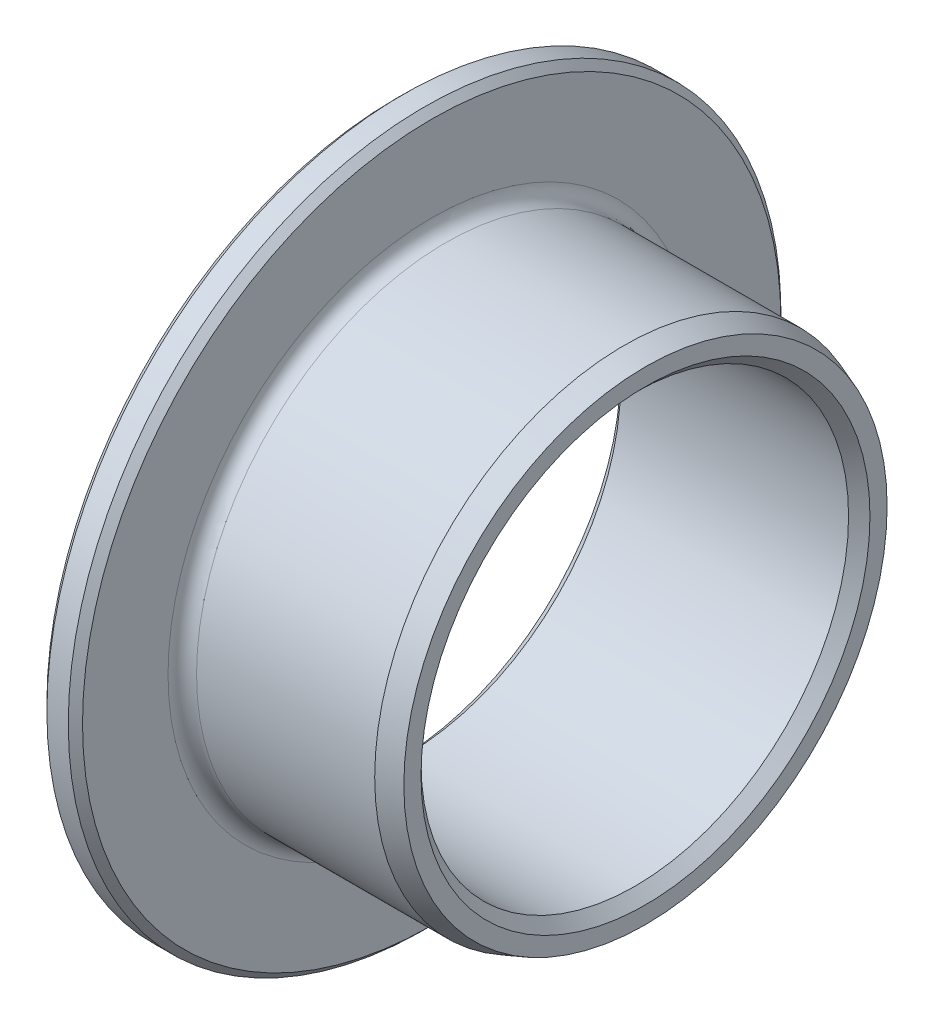
SolidWorks part; units mm, degrees
ref_plane "Face" through (0, 0, 0) normal (0, 0, 1) x (1, 0, 0)
ref_plane "Dessus" through (0, 0, 0) normal (0, 1, 0) x (1, 0, 0)
ref_plane "Droite" through (0, 0, 0) normal (1, 0, 0) x (0, 0, -1)
sketch "Esquisse1" plane through (0, 0, 0) normal (0, 0, 1) x (1, 0, 0)
  line L0 (-1, 6) -> (-1, 10)
  line L1 (-1, 10) -> (0, 10)
  line L2 (0, 10) -> (0, 7)
  line L3 (0, 7) -> (6, 7)
  line L4 (6, 7) -> (6, 6)
  line L5 (6, 6) -> (-1, 6)
  line L6 (-5.3127, 0) -> (18.9323, 0) construction
  dimension "D1" = 10
  dimension "D2" = 6
  dimension "D3" = 1
  dimension "D4" = 7
  dimension "D5" = 7
revolve "Base-Révolution" add sketch "Esquisse1" angle 360 about L6
chamfer "Chanfrein2" distance 0.6 angle 20 1 edges at (6, 0, 7)
chamfer "Chanfrein3" distance 0.3 angle 45 2 edges at (-1, 0, 6) (6, 0, 6)
chamfer "Chanfrein4" distance 0.2 angle 45 2 edges at (0, 0, 10) (-1, 0, 10)
fillet "Congé1" radius 0.4 1 edges at (0, 0, 7)
